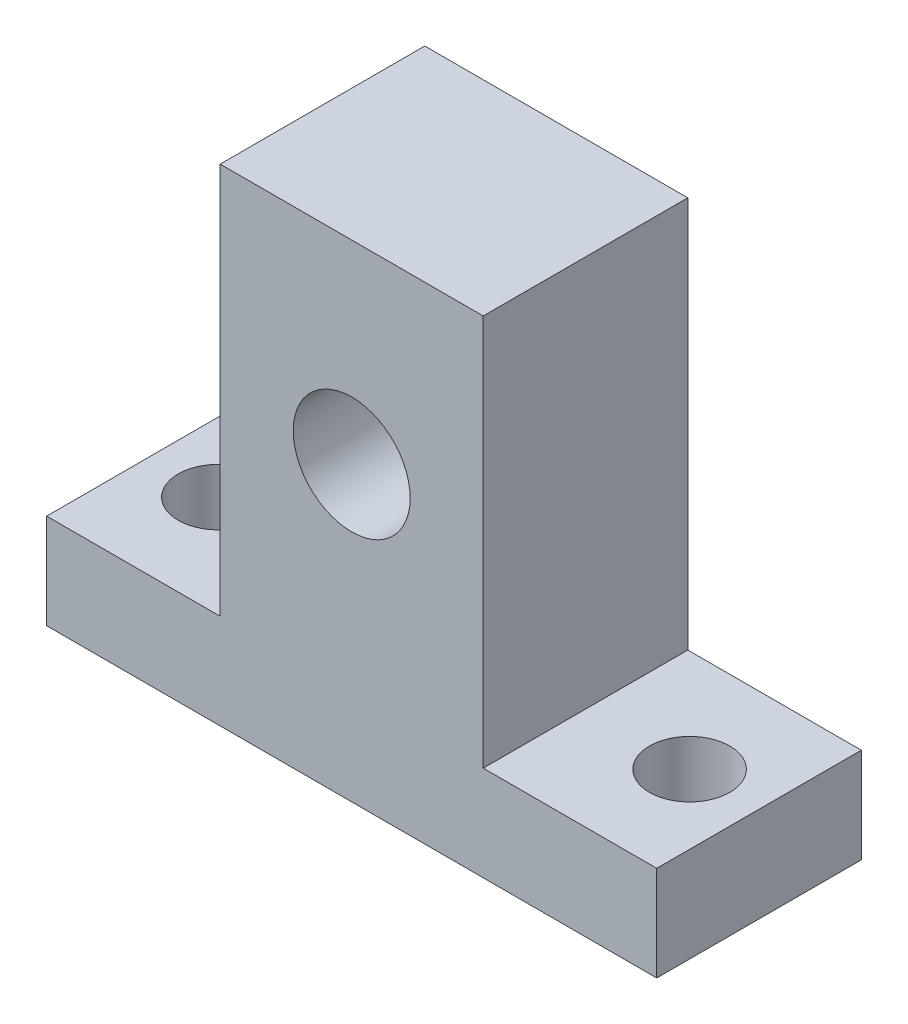
SolidWorks part; units mm, degrees
ref_plane "Front Plane" through (0, 0, 0) normal (0, 0, 1) x (1, 0, 0)
ref_plane "Top Plane" through (0, 0, 0) normal (0, 1, 0) x (1, 0, 0)
ref_plane "Right Plane" through (0, 0, 0) normal (1, 0, 0) x (0, 0, -1)
sketch "Sketch1" plane through (0, 0, 0) normal (0, 1, 0) x (1, 0, 0)
  line L1 (0, 0) -> (41.75, 0)
  line L2 (0, 0) -> (0, 14)
  line L3 (0, 14) -> (41.75, 14)
  line L4 (41.75, 0) -> (41.75, 14)
  dimension "D1" = 14
  dimension "D2" = 41.75
extrude "Boss-Extrude1" add sketch "Sketch1" along normal blind 6.5
sketch "Sketch2" plane through (0, 6.5, 0) normal (0, 1, 0) x (1, 0, 0)
  line L0 (0, 0) -> (41.75, 0) construction
  line L1 (11.875, 0) -> (29.875, 0)
  line L2 (11.875, 0) -> (11.875, 14)
  line L3 (11.875, 14) -> (29.875, 14)
  line L4 (29.875, 0) -> (29.875, 14)
  line L5 (41.75, 14) -> (0, 14) construction
  line L6 (20.875, 14) -> (20.875, 0) construction
  line L7 (20.875, 14) -> (20.875, 0) construction
  dimension "D1" = 18
extrude "Boss-Extrude2" add sketch "Sketch2" along normal blind 26.8
sketch "Sketch3" plane through (0, 0, 0) normal (0, 0, 1) x (1, 0, 0)
  line L0 (0, 0) -> (41.75, 0) construction
  line L1 (20.875, 33.3) -> (20.875, 0) construction
  line L2 (11.875, 33.3) -> (29.875, 33.3) construction
  circle A0 centre (20.875, 20) radius 4
  dimension "D1" = 8
  dimension "D2" = 20
extrude "Cut-Extrude1" cut sketch "Sketch3" against normal through all and the other way through all
sketch "Sketch4" plane through (0, 6.5, 0) normal (0, 1, 0) x (1, 0, 0)
  line L0 (41.75, 0) -> (41.75, 14) construction
  line L1 (41.75, 7) -> (0, 7) construction
  line L2 (0, 14) -> (0, 0) construction
  line L5 (20.875, 7) -> (20.875, 0) construction
  circle A0 centre (37, 7) radius 2.75
  circle A1 centre (4.75, 7) radius 2.75
  dimension "D1" = 5.5
  dimension "D2" = 4.75
extrude "Cut-Extrude2" cut sketch "Sketch4" against normal through all
